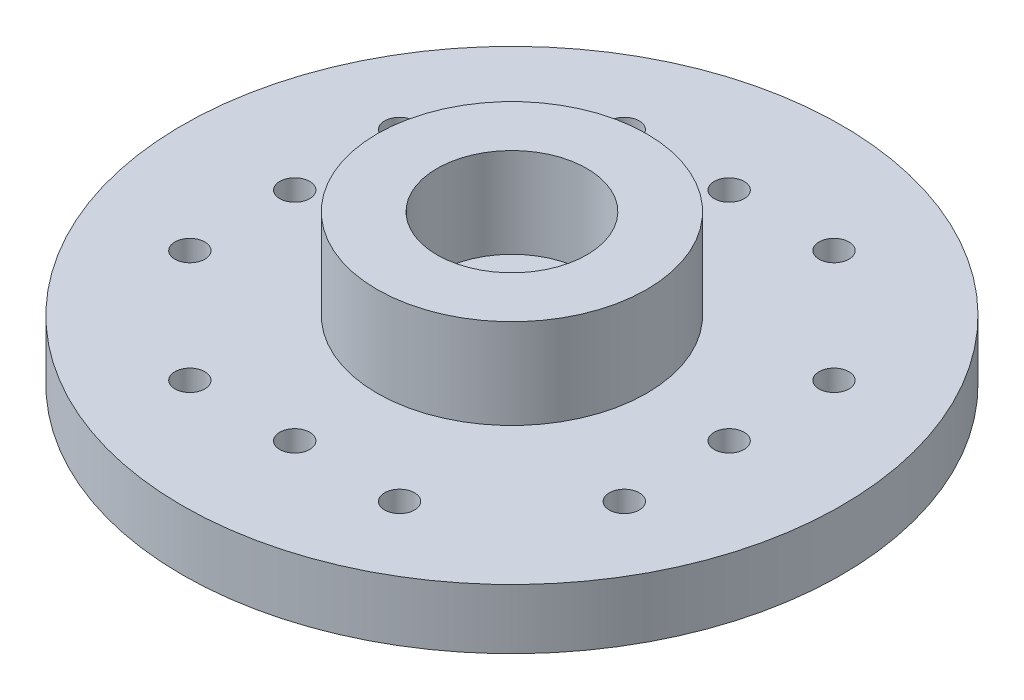
SolidWorks part; units mm, degrees
ref_plane "Front" through (0, 0, 0) normal (0, 0, 1) x (1, 0, 0)
ref_plane "Top" through (0, 0, 0) normal (0, 1, 0) x (1, 0, 0)
ref_plane "Right" through (0, 0, 0) normal (1, 0, 0) x (0, 0, -1)
sketch "Sketch1" plane through (0, 0, 0) normal (0, 1, 0) x (1, 0, 0)
  circle A0 centre (0, 0) radius 11
  circle A1 centre (0, 0) radius 1.5
  dimension "D1" = 22
  dimension "D2" = 3
extrude "Boss-Extrude1" add sketch "Sketch1" along normal blind 2
sketch "Sketch2" plane through (0, 2, 0) normal (0, 1, 0) x (1, 0, 0)
  circle A0 centre (0, 0) radius 4.5
  circle A1 centre (0, 0) radius 2.5
  dimension "D1" = 9
  dimension "D2" = 5
extrude "Boss-Extrude2" add sketch "Sketch2" along normal blind 3
sketch "Sketch3" plane through (0, 2, 0) normal (0, 1, 0) x (1, 0, 0)
  line L0 (-3.5, 7.25) -> (0, 7.25) construction
  line L1 (0, 7.25) -> (3.5, 7.25) construction
  circle A0 centre (-3.5, 7.25) radius 0.5
  circle A1 centre (0, 7.25) radius 0.5
  circle A2 centre (3.5, 7.25) radius 0.5
  point P6 (4.6048, 7.1124)
  point P7 (0, 0)
  dimension "D2" = 1
  dimension "D1" = 7.25
  dimension "D3" = 7
extrude "Cut-Extrude1" cut sketch "Sketch3" against normal through all
pattern_circular "CirPattern1" count 4 over 360 about axis through (0, 0, 0) along (0, 1, 0) of "Cut-Extrude1"
